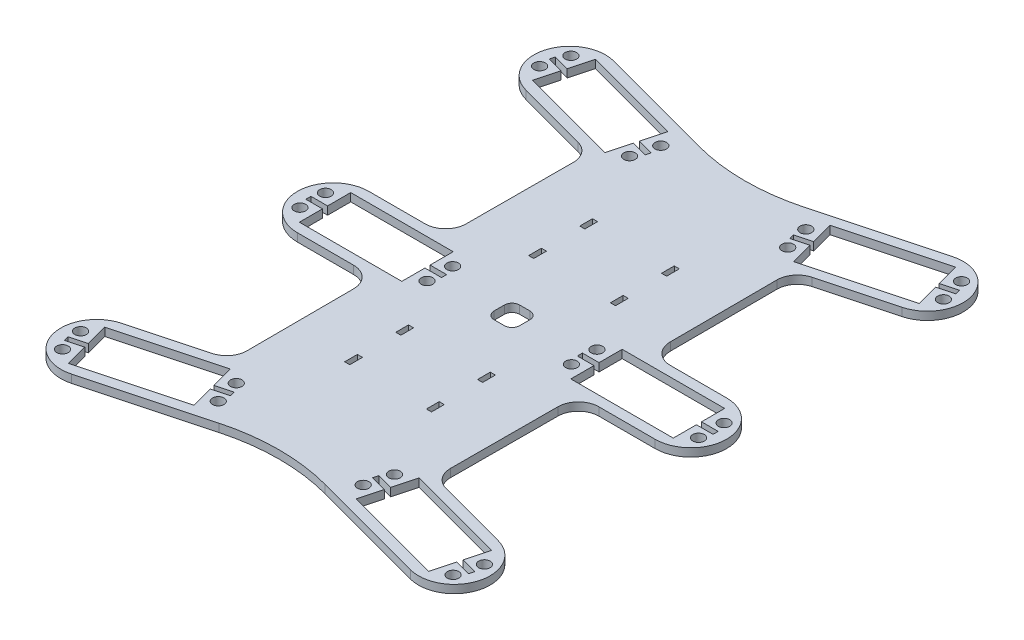
SolidWorks part; units mm, degrees
ref_plane "Front Plane" through (0, 0, 0) normal (0, 0, 1) x (1, 0, 0)
ref_plane "Top Plane" through (0, 0, 0) normal (0, 1, 0) x (1, 0, 0)
ref_plane "Right Plane" through (0, 0, 0) normal (1, 0, 0) x (0, 0, -1)
sketch "Sketch1" plane through (0, 0, 0) normal (0, 1, 0) x (1, 0, 0)
  line L0 (0, 32.1883) -> (0, -21.4181) construction
  line L1 (0, 0) -> (27.1703, 0) construction
  line L2 (-70, 14) -> (-40, 14)
  line L3 (-40, 14) -> (-39.8161, 70)
  line L4 (-39.8161, 70) -> (-73.6235, 79.0587)
  line L5 (-66.3765, 106.1046) -> (0, 88.3191)
  line L10 (-66.3765, 106.1046) -> (-73.6235, 79.0587) construction
  line L12 (-70, 14) -> (-70, -14) construction
  line L14 (-66.3765, -106.1046) -> (0, -88.3191)
  line L15 (-39.8161, -70) -> (-73.6235, -79.0587)
  line L16 (-40, -14) -> (-39.8161, -70)
  line L17 (-70, -14) -> (-40, -14)
  line L18 (66.3765, -106.1046) -> (0, -88.3191)
  line L19 (66.3765, 106.1046) -> (0, 88.3191)
  line L20 (70, 14) -> (70, -14) construction
  line L21 (66.3765, 106.1046) -> (73.6235, 79.0587) construction
  line L22 (70, -14) -> (40, -14)
  line L23 (40, -14) -> (39.8161, -70)
  line L24 (39.8161, -70) -> (73.6235, -79.0587)
  line L25 (39.8161, 70) -> (73.6235, 79.0587)
  line L26 (40, 14) -> (39.8161, 70)
  line L27 (70, 14) -> (40, 14)
  line L28 (-70.4609, 103.1096) -> (-75.6631, 83.6945)
  line L29 (-75.6631, 83.6945) -> (-36.9295, 73.3159)
  line L30 (-36.9295, 73.3159) -> (-31.7272, 92.731)
  line L31 (-31.7272, 92.731) -> (-70.4609, 103.1096)
  line L32 (-51.094, 97.9203) -> (-56.2963, 78.5052) construction
  line L33 (-70, 92.5816) -> (-73.062, 93.4021) construction
  line L34 (-53.12, 10.05) -> (-53.12, -10.05) construction
  line L35 (-73.17, 10.05) -> (-33.07, 10.05)
  line L36 (-73.17, 10.05) -> (-73.17, -10.05)
  line L37 (-73.17, -10.05) -> (-33.07, -10.05)
  line L38 (-33.07, 10.05) -> (-33.07, -10.05)
  line L39 (-73.17, 10.05) -> (-33.07, -10.05) construction
  line L40 (-73.17, -10.05) -> (-33.07, 10.05) construction
  line L41 (-36.9295, -73.3159) -> (-31.7272, -92.731)
  line L42 (-31.7272, -92.731) -> (-70.4609, -103.1096)
  line L43 (-70.4609, -103.1096) -> (-75.6631, -83.6945)
  line L44 (-75.6631, -83.6945) -> (-36.9295, -73.3159)
  line L45 (36.9295, 73.3159) -> (31.7272, 92.731)
  line L46 (75.6631, 83.6945) -> (36.9295, 73.3159)
  line L47 (70.4609, 103.1096) -> (75.6631, 83.6945)
  line L48 (31.7272, 92.731) -> (70.4609, 103.1096)
  line L49 (73.17, -10.05) -> (33.07, 10.05) construction
  line L50 (73.17, 10.05) -> (33.07, -10.05) construction
  line L51 (53.12, 10.05) -> (53.12, -10.05) construction
  line L52 (33.07, 10.05) -> (33.07, -10.05)
  line L53 (73.17, -10.05) -> (33.07, -10.05)
  line L54 (73.17, 10.05) -> (73.17, -10.05)
  line L55 (73.17, 10.05) -> (33.07, 10.05)
  line L56 (36.9295, -73.3159) -> (31.7272, -92.731)
  line L57 (75.6631, -83.6945) -> (36.9295, -73.3159)
  line L58 (31.7272, -92.731) -> (70.4609, -103.1096)
  line L59 (70.4609, -103.1096) -> (75.6631, -83.6945)
  line L60 (-76.4333, 99.4818) -> (-79.0215, 89.8226) construction
  line L61 (-77.7274, 94.6522) -> (-70, 92.5816) construction
  line L62 (-78, 5) -> (-78, -5) construction
  arc A0 (-70, 14) -> (-70, -14) centre (-70, 0) ccw
  arc A1 (-66.3765, 106.1046) -> (-73.6235, 79.0587) centre (-70, 92.5816) ccw
  circle A8 centre (-76.4333, 99.4818) radius 2.25
  circle A9 centre (-79.0215, 89.8226) radius 2.25
  circle A10 centre (-78, 5) radius 2.25
  arc A11 (-66.3765, -106.1046) -> (-73.6235, -79.0587) centre (-70, -92.5816) cw
  circle A12 centre (-79.0215, -89.8226) radius 2.25
  circle A13 centre (-76.4333, -99.4818) radius 2.25
  circle A14 centre (-78, -5) radius 2.25
  circle A15 centre (78, -5) radius 2.25
  circle A16 centre (76.4333, -99.4818) radius 2.25
  circle A17 centre (79.0215, -89.8226) radius 2.25
  arc A18 (66.3765, -106.1046) -> (73.6235, -79.0587) centre (70, -92.5816) ccw
  circle A19 centre (78, 5) radius 2.25
  circle A20 centre (79.0215, 89.8226) radius 2.25
  circle A21 centre (76.4333, 99.4818) radius 2.25
  arc A22 (66.3765, 106.1046) -> (73.6235, 79.0587) centre (70, 92.5816) cw
  arc A23 (70, 14) -> (70, -14) centre (70, 0) cw
  circle A24 centre (-30.957, 76.9437) radius 2.25
  circle A25 centre (-28.3688, 86.603) radius 2.25
  circle A26 centre (-28.24, -5) radius 2.25
  circle A27 centre (-28.24, 5) radius 2.25
  circle A28 centre (-28.3688, -86.603) radius 2.25
  circle A29 centre (-30.957, -76.9437) radius 2.25
  circle A30 centre (28.3688, 86.603) radius 2.25
  circle A31 centre (30.957, 76.9437) radius 2.25
  circle A32 centre (28.24, 5) radius 2.25
  circle A33 centre (28.24, -5) radius 2.25
  circle A34 centre (30.957, -76.9437) radius 2.25
  circle A35 centre (28.3688, -86.603) radius 2.25
  point P60 (-51.094, 97.9203)
  point P62 (-56.2963, 78.5052)
  point P65 (-73.062, 93.4021)
  point P71 (-53.12, 0)
  point P108 (53.12, 0)
  point P118 (-83.523, 96.2051)
  dimension "D2" = 14
  dimension "D3" = 10
  dimension "D8" = 4.5
  dimension "D1" = 75
  dimension "D4" = 70
  dimension "D5" = 30
  dimension "D6" = 35
  dimension "D7" = 56
  dimension "D9" = 8
  dimension "D10" = 5
  dimension "D11" = 10
  dimension "D12" = 40.1
  dimension "D13" = 20.1
  dimension "D14" = 4.83
  dimension "D15" = 40.1
  dimension "D16" = 20.1
  dimension "D17" = 4.83
  dimension "D18" = 8
extrude "Boss-Extrude1" add sketch "Sketch1" along normal blind 3.175
fillet "Fillet1" radius 80 2 edges at (0, 1.5875, -88.3191) (0, 1.5875, 88.3191)
fillet "Fillet2" radius 8 8 edges at (39.8161, 1.5875, 70) (40, 1.5875, 14) (40, 1.5875, -14) (39.8161, 1.5875, -70) (-39.8161, 1.5875, -70) (-40, 1.5875, -14) (-40, 1.5875, 14) (-39.8161, 1.5875, 70)
sketch "Sketch5" plane through (0, 3.175, 0) normal (0, 1, 0) x (1, 0, 0)
  line L0 (0, 91.1411) -> (0, -91.1411) construction
  line L1 (-84, 0) -> (84, 0) construction
  line L2 (-33.07, -10.05) -> (-33.07, 10.05) construction
  line L3 (-33.07, 1) -> (-26.57, 1)
  line L4 (-33.07, 1) -> (-33.07, -1)
  line L5 (-33.07, -1) -> (-26.57, -1)
  line L6 (-26.57, 1) -> (-26.57, -1)
  line L7 (-33.07, 1) -> (-26.57, -1) construction
  line L8 (-33.07, -1) -> (-26.57, 1) construction
  line L9 (-33.07, 10.05) -> (-73.17, 10.05) construction
  line L10 (-53.12, 10.05) -> (-53.12, -10.05) construction
  line L11 (-73.17, -10.05) -> (-33.07, -10.05) construction
  line L12 (-73.17, -1) -> (-79.67, 1) construction
  line L13 (-73.17, 1) -> (-79.67, -1) construction
  line L14 (-79.67, 1) -> (-79.67, -1)
  line L15 (-73.17, -1) -> (-79.67, -1)
  line L16 (-73.17, 1) -> (-73.17, -1)
  line L17 (-73.17, 1) -> (-79.67, 1)
  line L18 (-34.0695, 83.9894) -> (-27.791, 82.307)
  line L19 (-36.9295, 73.3159) -> (-31.7272, 92.731) construction
  line L20 (-27.791, 82.307) -> (-28.3087, 80.3752)
  line L21 (-28.3087, 80.3752) -> (-34.5872, 82.0575)
  line L22 (-34.0695, 83.9894) -> (-34.5872, 82.0575)
  line L23 (-51.094, 97.9203) -> (-56.2963, 78.5052) construction
  line L24 (-31.7272, 92.731) -> (-70.4609, 103.1096) construction
  line L25 (-75.6631, 83.6945) -> (-36.9295, 73.3159) construction
  line L26 (-72.8032, 94.368) -> (-73.3208, 92.4362)
  line L27 (-79.5993, 94.1185) -> (-73.3208, 92.4362)
  line L28 (-79.0817, 96.0503) -> (-79.5993, 94.1185)
  line L29 (-72.8032, 94.368) -> (-79.0817, 96.0503)
  line L30 (51.094, 97.9203) -> (56.2963, 78.5052) construction
  line L31 (72.8032, 94.368) -> (79.0817, 96.0503)
  line L32 (79.0817, 96.0503) -> (79.5993, 94.1185)
  line L33 (79.5993, 94.1185) -> (73.3208, 92.4362)
  line L34 (72.8032, 94.368) -> (73.3208, 92.4362)
  line L35 (34.0695, 83.9894) -> (34.5872, 82.0575)
  line L36 (28.3087, 80.3752) -> (34.5872, 82.0575)
  line L37 (27.791, 82.307) -> (28.3087, 80.3752)
  line L38 (34.0695, 83.9894) -> (27.791, 82.307)
  line L39 (73.17, 1) -> (79.67, -1) construction
  line L40 (73.17, -1) -> (79.67, 1) construction
  line L41 (53.12, 10.05) -> (53.12, -10.05) construction
  line L42 (33.07, -1) -> (26.57, 1) construction
  line L43 (33.07, 1) -> (26.57, -1) construction
  line L44 (73.17, 1) -> (79.67, 1)
  line L45 (73.17, 1) -> (73.17, -1)
  line L46 (73.17, -1) -> (79.67, -1)
  line L47 (79.67, 1) -> (79.67, -1)
  line L48 (26.57, 1) -> (26.57, -1)
  line L49 (33.07, -1) -> (26.57, -1)
  line L50 (33.07, 1) -> (33.07, -1)
  line L51 (33.07, 1) -> (26.57, 1)
  line L52 (51.094, -97.9203) -> (56.2963, -78.5052) construction
  line L53 (-51.094, -97.9203) -> (-56.2963, -78.5052) construction
  line L54 (34.0695, -83.9894) -> (27.791, -82.307)
  line L55 (27.791, -82.307) -> (28.3087, -80.3752)
  line L56 (28.3087, -80.3752) -> (34.5872, -82.0575)
  line L57 (34.0695, -83.9894) -> (34.5872, -82.0575)
  line L58 (72.8032, -94.368) -> (73.3208, -92.4362)
  line L59 (79.5993, -94.1185) -> (73.3208, -92.4362)
  line L60 (79.0817, -96.0503) -> (79.5993, -94.1185)
  line L61 (72.8032, -94.368) -> (79.0817, -96.0503)
  line L62 (-72.8032, -94.368) -> (-79.0817, -96.0503)
  line L63 (-79.0817, -96.0503) -> (-79.5993, -94.1185)
  line L64 (-79.5993, -94.1185) -> (-73.3208, -92.4362)
  line L65 (-72.8032, -94.368) -> (-73.3208, -92.4362)
  line L66 (-34.0695, -83.9894) -> (-34.5872, -82.0575)
  line L67 (-28.3087, -80.3752) -> (-34.5872, -82.0575)
  line L68 (-27.791, -82.307) -> (-28.3087, -80.3752)
  line L69 (-34.0695, -83.9894) -> (-27.791, -82.307)
  arc A0 (-20.7055, 93.8671) -> (20.7055, 93.8671) centre (0, 171.1411) ccw construction
  arc A1 (20.7055, -93.8671) -> (-20.7055, -93.8671) centre (0, -171.1411) ccw construction
  arc A2 (-70, 14) -> (-70, -14) centre (-70, 0) ccw construction
  arc A3 (70, -14) -> (70, 14) centre (70, 0) ccw construction
  point P16 (-29.82, 0)
  point P23 (-53.12, 10.05)
  point P34 (-76.42, 0)
  point P39 (-34.3284, 83.0234)
  point P42 (-34.3284, 83.0234)
  point P53 (-73.062, 93.4021)
  point P64 (73.062, 93.4021)
  point P65 (34.3284, 83.0234)
  point P76 (76.42, 0)
  point P77 (29.82, 0)
  point P98 (34.3284, -83.0234)
  point P99 (73.062, -93.4021)
  point P100 (-73.062, -93.4021)
  point P101 (-34.3284, -83.0234)
  dimension "D1" = 2
  dimension "D2" = 6.5
  dimension "D3" = 2
  dimension "D4" = 6.5
extrude "Cut-Extrude2" cut sketch "Sketch5" against normal through all
sketch "Sketch6" plane through (0, 3.175, 0) normal (0, 1, 0) x (1, 0, 0)
  line L0 (-84, 0) -> (84, 0) construction
  line L1 (0, -91.1411) -> (0, 91.1411) construction
  line L2 (17, -48.5) -> (15, -43.5) construction
  line L3 (-17, -23.5) -> (-15, -23.5)
  line L4 (-17, -23.5) -> (-17, -28.5)
  line L5 (-17, -28.5) -> (-15, -28.5)
  line L6 (-15, -23.5) -> (-15, -28.5)
  line L7 (-17, -23.5) -> (-15, -28.5) construction
  line L8 (-17, -28.5) -> (-15, -23.5) construction
  line L9 (-17, -43.5) -> (-15, -43.5)
  line L10 (-17, -43.5) -> (-17, -48.5)
  line L11 (-17, -48.5) -> (-15, -48.5)
  line L12 (-15, -43.5) -> (-15, -48.5)
  line L13 (-17, -43.5) -> (-15, -48.5) construction
  line L14 (-17, -48.5) -> (-15, -43.5) construction
  line L15 (17, -43.5) -> (15, -48.5) construction
  line L16 (17, -28.5) -> (15, -23.5) construction
  line L17 (17, -23.5) -> (15, -28.5) construction
  line L18 (15, -43.5) -> (15, -48.5)
  line L19 (17, -48.5) -> (15, -48.5)
  line L20 (17, -43.5) -> (17, -48.5)
  line L21 (17, -43.5) -> (15, -43.5)
  line L22 (15, -23.5) -> (15, -28.5)
  line L23 (17, -28.5) -> (15, -28.5)
  line L24 (17, -23.5) -> (17, -28.5)
  line L25 (17, -23.5) -> (15, -23.5)
  line L26 (17, 23.5) -> (15, 28.5) construction
  line L27 (17, 28.5) -> (15, 23.5) construction
  line L28 (17, 43.5) -> (15, 48.5) construction
  line L29 (-17, 48.5) -> (-15, 43.5) construction
  line L30 (-17, 43.5) -> (-15, 48.5) construction
  line L31 (-17, 28.5) -> (-15, 23.5) construction
  line L32 (-17, 23.5) -> (-15, 28.5) construction
  line L33 (17, 48.5) -> (15, 43.5) construction
  line L34 (17, 23.5) -> (15, 23.5)
  line L35 (17, 23.5) -> (17, 28.5)
  line L36 (17, 28.5) -> (15, 28.5)
  line L37 (15, 23.5) -> (15, 28.5)
  line L38 (17, 43.5) -> (15, 43.5)
  line L39 (17, 43.5) -> (17, 48.5)
  line L40 (17, 48.5) -> (15, 48.5)
  line L41 (15, 43.5) -> (15, 48.5)
  line L42 (-15, 43.5) -> (-15, 48.5)
  line L43 (-17, 48.5) -> (-15, 48.5)
  line L44 (-17, 43.5) -> (-17, 48.5)
  line L45 (-17, 43.5) -> (-15, 43.5)
  line L46 (-15, 23.5) -> (-15, 28.5)
  line L47 (-17, 28.5) -> (-15, 28.5)
  line L48 (-17, 23.5) -> (-17, 28.5)
  line L49 (-17, 23.5) -> (-15, 23.5)
  line L51 (-5, 5) -> (5, 5)
  line L52 (-5, 5) -> (-5, -5)
  line L53 (-5, -5) -> (5, -5)
  line L54 (5, 5) -> (5, -5)
  line L55 (-5, 5) -> (5, -5) construction
  line L56 (-5, -5) -> (5, 5) construction
  arc A0 (-70, 14) -> (-70, -14) centre (-70, 0) ccw construction
  arc A1 (70, -14) -> (70, 14) centre (70, 0) ccw construction
  arc A2 (20.7055, -93.8671) -> (-20.7055, -93.8671) centre (0, -171.1411) ccw construction
  arc A3 (-20.7055, 93.8671) -> (20.7055, 93.8671) centre (0, 171.1411) ccw construction
  point P16 (-16, -26)
  point P21 (-16, -46)
  point P34 (16, -46)
  point P35 (16, -26)
  point P52 (16, 26)
  point P53 (16, 46)
  point P54 (-16, 46)
  point P55 (-16, 26)
  point P56 (0, 0)
  dimension "D1" = 16
  dimension "D2" = 5
  dimension "D3" = 2
  dimension "D4" = 20
  dimension "D5" = 26
  dimension "D6" = 10
  dimension "D7" = 10
extrude "Cut-Extrude3" cut sketch "Sketch6" against normal blind 10
fillet "Fillet3" radius 3 4 edges at (-5, 1.5875, 5) (5, 1.5875, 5) (-5, 1.5875, -5) (5, 1.5875, -5)
